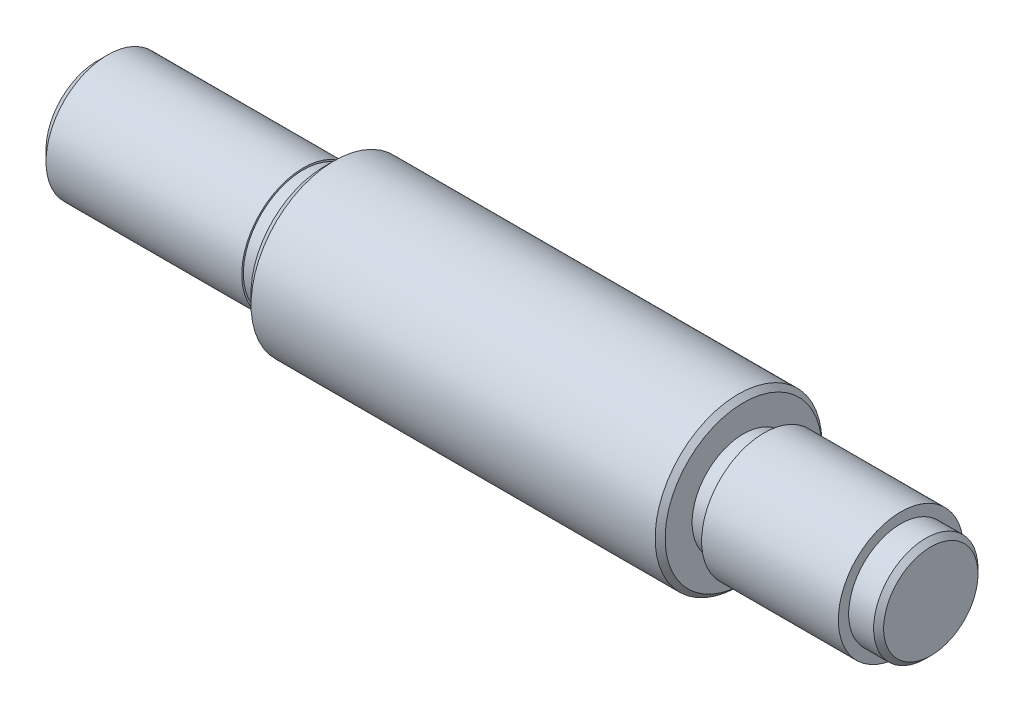
SolidWorks part; units mm, degrees
ref_plane "Front Plane" through (0, 0, 0) normal (0, 0, 1) x (1, 0, 0)
ref_plane "Top Plane" through (0, 0, 0) normal (0, 1, 0) x (1, 0, 0)
ref_plane "Right Plane" through (0, 0, 0) normal (1, 0, 0) x (0, 0, -1)
sketch "Sketch1" plane through (0, 0, 0) normal (1, 0, 0) x (0, 0, -1)
  circle A0 centre (0, 0) radius 3.9116
  dimension "D1" = 7.8232
extrude "Boss-Extrude1" add sketch "Sketch1" along normal mid plane 63.5
sketch "Sketch2" plane through (-31.75, 0, 0) normal (-1, 0, 0) x (0, 0, 1)
  circle A0 centre (0, 0) radius 4.699
  dimension "D1" = 9.398
extrude "Boss-Extrude2" add sketch "Sketch2" against normal blind 17.272
sketch "Sketch3" plane through (-14.478, 0, 0) normal (1, 0, 0) x (0, 0, -1)
  circle A0 centre (0, 0) radius 4.699
  circle A1 centre (0, 0) radius 4.572
  circle A2 centre (0, 0) radius 4.699 construction
  dimension "D1" = 9.144
extrude "Cut-Extrude1" cut sketch "Sketch3" against normal blind 1.5748
sketch "Sketch6" plane through (31.75, 0, 0) normal (1, 0, 0) x (0, 0, -1)
  circle A0 centre (0, 0) radius 4.7625
  dimension "D1" = 9.525
extrude "Boss-Extrude4" add sketch "Sketch6" against normal blind 12.7
sketch "Sketch5" plane through (31.75, 0, 0) normal (1, 0, 0) x (0, 0, -1)
  circle A0 centre (0, 0) radius 3.9751
  dimension "D1" = 7.9502
sketch "Sketch7" plane through (31.75, 0, 0) normal (1, 0, 0) x (0, 0, -1)
  circle A0 centre (0, 0) radius 4.7625
  circle A1 centre (0, 0) radius 3.9751
  dimension "D1" = 7.9502
  dimension "D2" = 9.525
extrude "Cut-Extrude2" cut sketch "Sketch7" against normal blind 2.286
sketch "Sketch8" plane through (-14.478, 0, 0) normal (1, 0, 0) x (0, 0, -1)
  circle A0 centre (0, 0) radius 6.35
  dimension "D1" = 12.7
extrude "Boss-Extrude5" add sketch "Sketch8" along normal offset from surface (31.9532 mm away) 1.5748 up to face at (19.05, 0, -3.9116)
chamfer "Chamfer1" distance 0.7874 angle 45 2 edges at (-14.478, 0, -6.35) (-31.75, 0, 4.699)
chamfer "Chamfer2" distance 0.381 angle 45 2 edges at (31.75, 0, -3.9751) (17.4752, 0, -6.35)
